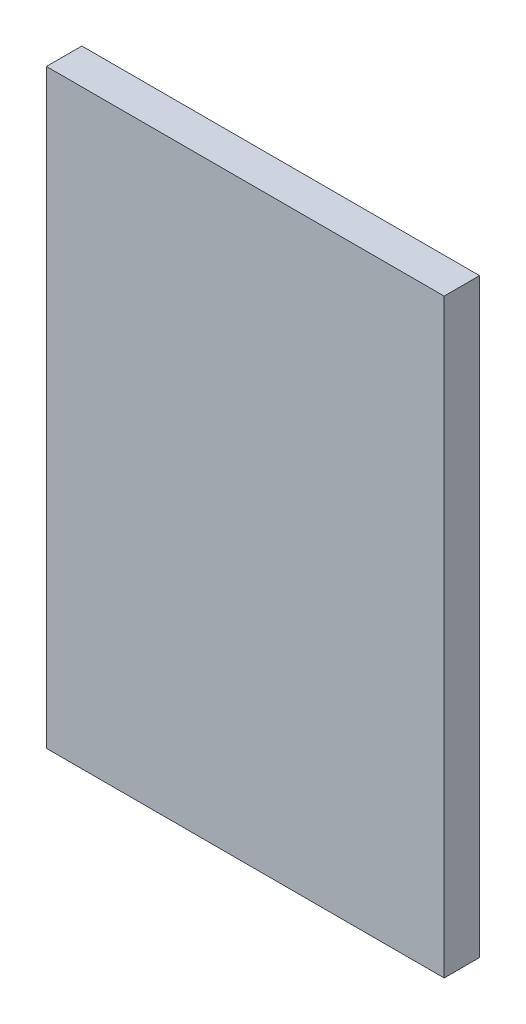
SolidWorks part; units mm, degrees
ref_plane "Front Plane" through (0, 0, 0) normal (0, 0, 1) x (1, 0, 0)
ref_plane "Top Plane" through (0, 0, 0) normal (0, 1, 0) x (1, 0, 0)
ref_plane "Right Plane" through (0, 0, 0) normal (1, 0, 0) x (0, 0, -1)
sketch "Sketch1" plane through (0, 0, 0) normal (0, 0, 1) x (1, 0, 0)
  line L1 (-99.822, 148.209) -> (99.822, 148.209)
  line L2 (-99.822, 148.209) -> (-99.822, -148.209)
  line L3 (-99.822, -148.209) -> (99.822, -148.209)
  line L4 (99.822, 148.209) -> (99.822, -148.209)
  line L5 (-99.822, 148.209) -> (99.822, -148.209) construction
  line L6 (-99.822, -148.209) -> (99.822, 148.209) construction
  point P0 (0, 0)
  dimension "D1" = 199.644
  dimension "D2" = 296.418
extrude "Boss-Extrude1" add sketch "Sketch1" along normal blind 17.78
